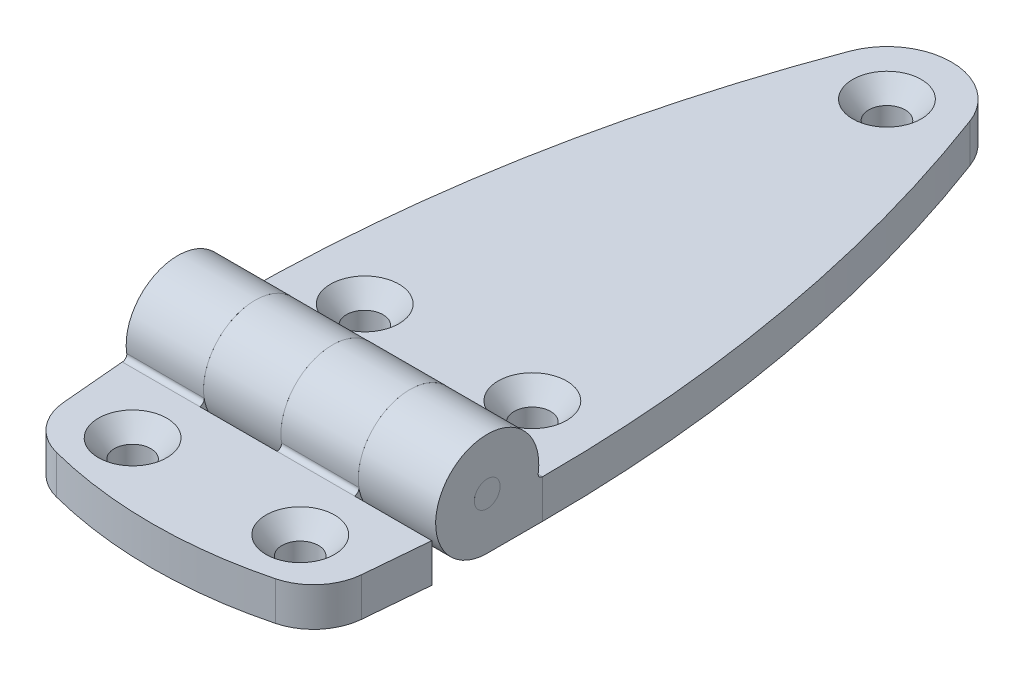
SolidWorks part; units mm, degrees
ref_plane "Front" through (0, 0, 0) normal (0, 0, 1) x (1, 0, 0)
ref_plane "Top" through (0, 0, 0) normal (0, 1, 0) x (1, 0, 0)
ref_plane "Right" through (0, 0, 0) normal (1, 0, 0) x (0, 0, -1)
sketch "Sketch1" plane through (0, 0, 0) normal (1, 0, 0) x (0, 0, -1)
  line L0 (0, 0) -> (-22.225, 0)
  line L1 (-22.225, 0) -> (-22.225, 4.7625)
  line L2 (-22.225, 4.7625) -> (0, 4.7625)
  line L3 (0, 4.7625) -> (76.2, 4.7625)
  line L4 (76.2, 4.7625) -> (76.2, 0)
  line L5 (76.2, 0) -> (0, 0)
  circle A0 centre (0, 6.35) radius 6.35
  circle A1 centre (0, 6.35) radius 1.5875
  dimension "D1" = 22.225
  dimension "Pin Dia" = 3.175
  dimension "Kn Dia" = 12.7
  dimension "Th" = 4.7625
  dimension "A" = 76.2
sketch "Sketch2" plane through (0, 0, 0) normal (1, 0, 0) x (0, 0, -1)
  line L0 (0, 0) -> (-22.225, 0)
  line L1 (-22.225, 0) -> (-22.225, 4.7625)
  line L2 (-22.225, 4.7625) -> (-6.8241, 4.7625)
  line L3 (-22.225, 4.7625) -> (0, 4.7625) construction
  arc A0 (0, 0) -> (-6.2782, 5.3975) centre (0, 6.35) ccw
  circle A1 centre (0, 6.35) radius 6.35 construction
  circle A2 centre (0, 6.35) radius 1.5875
  circle A3 centre (0, 6.35) radius 1.5875 construction
  arc A4 (-6.8241, 4.7625) -> (-6.2782, 5.3975) centre (-6.8241, 5.3147) ccw
  dimension "D1" = 0.635
extrude "Extrude1" add sketch "Sketch2" along normal mid plane 38.1
sketch "Sketch24" plane through (0, 0, 0) normal (0, 1, 0) x (1, 0, 0)
  line L0 (19.05, 6.35) -> (-19.05, 6.35) construction
  line L1 (-9.525, 6.35) -> (0, 6.35)
  line L2 (-9.525, 6.35) -> (-9.525, -6.8241)
  line L3 (-9.525, -6.8241) -> (0, -6.8241)
  line L4 (0, 6.35) -> (0, -6.8241)
  line L5 (9.525, 6.35) -> (19.05, 6.35)
  line L6 (9.525, 6.35) -> (9.525, -6.8241)
  line L7 (9.525, -6.8241) -> (19.05, -6.8241)
  line L8 (19.05, 6.35) -> (19.05, -6.8241)
  line L9 (19.05, -0.237) -> (9.525, -0.237) construction
  line L10 (9.525, -0.237) -> (0, -0.237) construction
  line L11 (0, -0.237) -> (-9.525, -0.237) construction
  line L12 (-9.525, -0.237) -> (-19.05, -0.237) construction
  line L13 (-19.05, 6.35) -> (-19.05, -6.35) construction
  line L16 (19.05, -6.8241) -> (-19.05, -6.8241) construction
extrude "Cut-Extrude5" cut sketch "Sketch24" along normal through all
sketch "Sketch4" plane through (0, 0, 0) normal (1, 0, 0) x (0, 0, -1)
  line L0 (0, 0) -> (76.2, 0)
  line L1 (76.2, 0) -> (76.2, 4.7625)
  line L2 (76.2, 4.7625) -> (6.8241, 4.7625)
  line L3 (0, 4.7625) -> (76.2, 4.7625) construction
  arc A0 (0, 0) -> (6.2782, 5.3975) centre (0, 6.35) cw
  circle A1 centre (0, 6.35) radius 6.35 construction
  circle A2 centre (0, 6.35) radius 1.5875
  circle A3 centre (0, 6.35) radius 1.5875 construction
  arc A4 (6.2782, 5.3975) -> (6.8241, 4.7625) centre (6.8241, 5.3147) ccw
  dimension "D1" = 0.635
extrude "Extrude2" add sketch "Sketch4" along normal up to surface and the other way up to surface separate body up to face at (19.05, 2.3812, 14.5245) other way up to face at (-19.05, 4.6527, 10.0255)
sketch "Sketch25" plane through (0, 0, 0) normal (0, 1, 0) x (1, 0, 0)
  line L0 (9.525, 6.35) -> (9.525, -6.8241) construction
  line L2 (-19.05, 6.8241) -> (-9.525, 6.8241)
  line L3 (-19.05, 6.8241) -> (-19.05, -6.35)
  line L4 (-19.05, -6.35) -> (-9.525, -6.35)
  line L5 (-9.525, 6.8241) -> (-9.525, -6.35)
  line L6 (0, 6.8241) -> (9.525, 6.8241)
  line L7 (0, 6.8241) -> (0, -6.35)
  line L8 (0, -6.35) -> (9.525, -6.35)
  line L9 (19.05, 6.8241) -> (-19.05, 6.8241) construction
  line L11 (-19.05, -6.35) -> (19.05, -6.35) construction
  line L12 (9.525, 6.8241) -> (9.525, -6.35)
extrude "Cut-Extrude6" cut sketch "Sketch25" along normal through all
ref_plane "Plane1" through (0, 6.35, 0) normal (0, 1, 0) x (-1, 0, 0)
sketch "Sketch7" plane through (0, 6.35, 0) normal (0, 1, 0) x (-1, 0, 0)
  line L0 (-19.05, 0) -> (19.05, 0)
  line L1 (-19.05, -1.5875) -> (-19.05, 0)
  line L2 (-19.05, -1.5875) -> (19.05, -1.5875)
  line L3 (19.05, -1.5875) -> (19.05, 0)
  point P5 (0, -1.5875)
revolve "Revolve1" add sketch "Sketch7" angle 360 about L0
sketch "Sketch8" plane through (0, 4.7625, 0) normal (0, 1, 0) x (-1, 0, 0)
  line L0 (-19.05, -76.2) -> (19.05, -76.2) construction
  line L1 (0, 0) -> (0, 22.225) construction
  line L2 (-19.05, -6.8241) -> (-22.1191, -6.8241)
  line L3 (-22.1191, -6.8241) -> (-22.1191, -80.1236)
  line L4 (-22.1191, -80.1236) -> (22.1191, -80.1236)
  line L5 (22.1191, -80.1236) -> (22.1191, -6.8241)
  line L6 (22.1191, -6.8241) -> (19.05, -6.8241)
  line L7 (19.05, -6.8241) -> (19.05, -76.2) construction
  line L8 (-19.05, 6.8241) -> (-18.3556, 14.7616)
  line L9 (19.05, 6.8241) -> (18.3556, 14.7616)
  line L10 (-19.05, -76.2) -> (-19.05, -6.8241) construction
  line L12 (19.05, 6.8241) -> (22.1191, 6.8241)
  line L13 (-19.05, 22.225) -> (19.05, 22.225) construction
  line L14 (-19.05, 6.8241) -> (-9.525, 6.8241) construction
  line L15 (9.525, -6.8241) -> (19.05, -6.8241) construction
  line L16 (19.05, 0) -> (-19.05, 0) construction
  line L17 (22.1191, 6.8241) -> (22.1191, 26.6001)
  line L18 (22.1191, 26.6001) -> (-22.1191, 26.6001)
  line L19 (-22.1191, 26.6001) -> (-22.1191, 6.8241)
  line L20 (-22.1191, 6.8241) -> (-19.05, 6.8241)
  line L24 (-19.05, -6.35) -> (-19.05, 6.8241) construction
  arc A1 (-7.4346, -71.0429) -> (7.4346, -71.0429) centre (0, -68.2625) ccw
  arc A2 (7.4346, -71.0429) -> (19.05, -6.8241) centre (-164.2831, -6.8241) ccw
  arc A3 (18.3556, 14.7616) -> (13.4938, 20.5063) centre (11.8591, 14.1932) ccw
  arc A4 (-19.05, -6.8241) -> (-7.4346, -71.0429) centre (164.2831, -6.8241) ccw
  arc A5 (-18.3556, 14.7616) -> (-13.4937, 20.5063) centre (-11.8591, 14.1932) cw
  arc A6 (-13.4937, 20.5063) -> (13.4938, 20.5063) centre (0, -31.6058) cw
  dimension "D1" = 7.9375
  dimension "D2" = 85
  dimension "D3" = 7.9375
  dimension "D4" = 26.9875
extrude "Cut-Extrude4" cut sketch "Sketch8" against normal blind 1056.132
sketch "Sketch9" plane through (0, 4.7625, 0) normal (0, 1, 0) x (-1, 0, 0)
  line L0 (19.05, -6.35) -> (19.05, 6.35) construction
  line L1 (19.05, 0) -> (-19.05, 0) construction
  line L4 (-19.05, -6.35) -> (-19.05, 6.8241) construction
  line L5 (0, -76.2) -> (0, 0) construction
  line L7 (0, -68.2625) -> (0, -76.2) construction
  point P20 (0, -68.2625)
  point P21 (10.3187, -14.2875)
  point P28 (-10.3188, -14.2875)
  point P33 (-10.3188, 14.2875)
  point P34 (10.3187, 14.2875)
  dimension "D1" = 20.6375
  dimension "D2" = 7.9375
  dimension "D3" = 53.975
hole_wizard "CSK for #8 Flat Head Machine Screw1" positions "Sketch14" profile "Sketch13" countersink size "#8" standard "Ansi Inch" end condition through all
sketch "Sketch14" plane through (-3.1926, 4.7625, 34.0762) normal (0, 1, 0) x (-1, 0, 0)
  point P31 (-3.1926, -102.3387)
  point P34 (7.1262, -48.3637)
  point P37 (-13.5113, -48.3637)
  point P40 (7.1262, -19.7887)
  point P43 (-13.5113, -19.7887)
sketch "Sketch13" plane through (0, 4.7625, -68.2625) normal (1, 0, 0) x (0, 0, 1)
  line L0 (0, 0) -> (0, 4.7625)
  line L1 (0, 4.7625) -> (2.2479, 4.7625)
  line L2 (2.2479, 4.7625) -> (2.2479, 2.2645)
  line L3 (2.2479, 2.2645) -> (4.2164, 0)
  line L5 (4.2164, 0) -> (0, 0)
  line L6 (-2.2479, 2.2645) -> (-4.2164, 0) construction
  line L11 (0, -6.35) -> (0, 107.95) construction
  dimension "Thru Hole Dia." = 4.4958
  dimension "Thru Hole Depth" = 4.7625
  dimension "Near C'Sink Dia." = 8.4328
  dimension "Near C'Sink Angle" = 82
